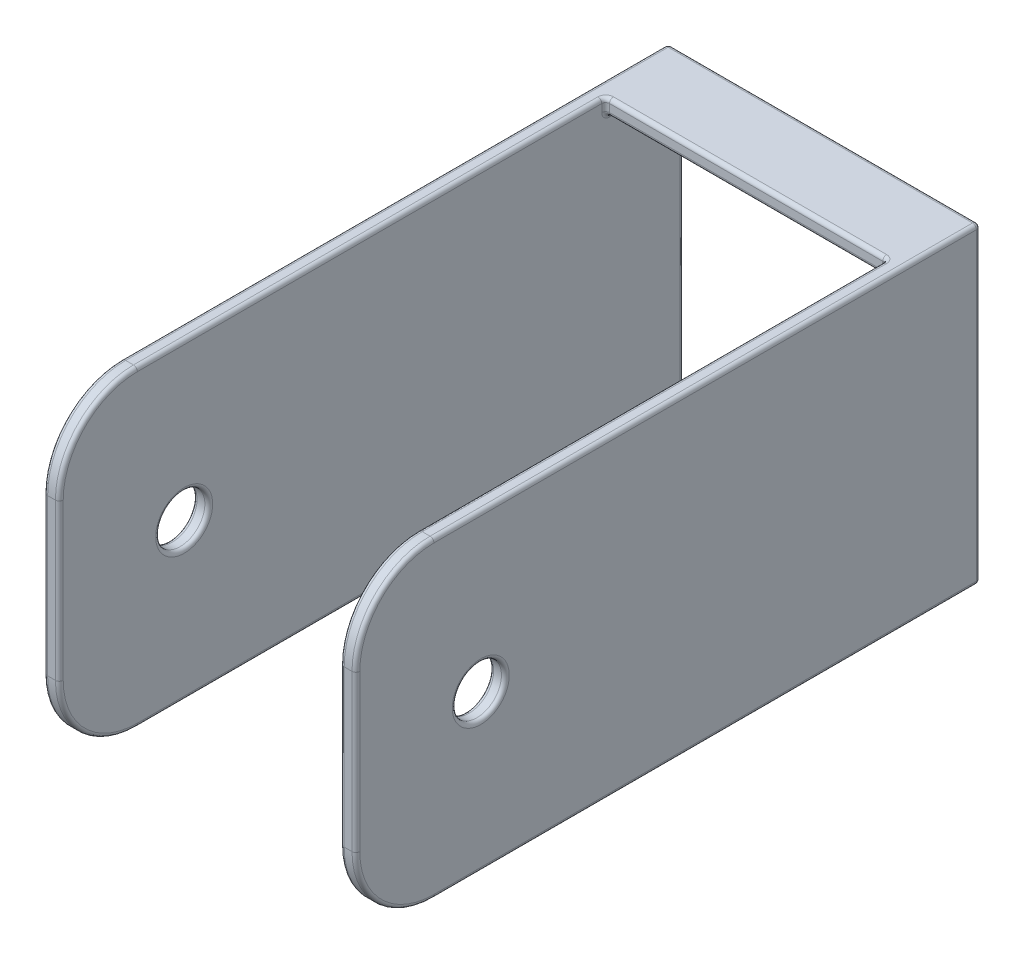
SolidWorks part; units mm, degrees
material "6061 Legierung"
ref_plane "Ebene vorne" through (0, 0, 0) normal (0, 0, 1) x (1, 0, 0)
ref_plane "Ebene oben" through (0, 0, 0) normal (0, 1, 0) x (1, 0, 0)
ref_plane "Ebene rechts" through (0, 0, 0) normal (1, 0, 0) x (0, 0, -1)
sketch "Skizze1" plane through (0, 0, 0) normal (0, 0, 1) x (1, 0, 0)
  line L1 (-20, -20) -> (20, -20)
  line L2 (-20, -20) -> (-20, 20)
  line L3 (-20, 20) -> (20, 20)
  line L4 (20, -20) -> (20, 20)
  line L5 (-20, -20) -> (20, 20) construction
  line L6 (-20, 20) -> (20, -20) construction
  line L7 (-18, -18) -> (18, -18)
  line L8 (-18, -18) -> (-18, 18)
  line L9 (-18, 18) -> (18, 18)
  line L10 (18, -18) -> (18, 18)
  line L11 (-18, -18) -> (18, 18) construction
  line L12 (-18, 18) -> (18, -18) construction
  point P0 (0, 0)
  point P6 (0, 0)
  dimension "D1" = 40
  dimension "D2" = 40
  dimension "D3" = 2
  dimension "D4" = 2
extrude "Aufsatz-Linear austragen1" add sketch "Skizze1" along normal blind 80
sketch "Skizze2" plane through (0, 20, 0) normal (0, 1, 0) x (1, 0, 0)
  line L0 (20, -80) -> (20, 0) construction
  line L1 (-18, -80) -> (18, -80)
  line L2 (-18, -80) -> (-18, -10)
  line L3 (-18, -10) -> (18, -10)
  line L4 (18, -80) -> (18, -10)
  line L5 (20, 0) -> (-20, 0) construction
  dimension "D1" = 2
  dimension "D2" = 10
extrude "Schnitt-Linear austragen1" cut sketch "Skizze2" against normal through all
sketch "Skizze3" plane through (20, 0, 0) normal (1, 0, 0) x (0, 0, -1)
  line L0 (-80, -20) -> (-80, 20) construction
  circle A0 centre (-64, 0) radius 3.15
  dimension "D1" = 6.3
  dimension "D2" = 16
extrude "Schnitt-Linear austragen2" cut sketch "Skizze3" against normal through all
fillet "Verrundung1" radius 10 4 edges at (-19, -20, 80) (19, -20, 80) (19, 20, 80) (-19, 20, 80)
fillet "Verrundung2" radius 0.5 44 edges at (0, -18, 0) (0, -18, 10) (0, 18, 0) (0, 18, 10) (-18, 17.0711, 77.0711) (-18, 19, 10) (-18, 18, 5) (-18, 0, 0) (-18, -18, 5) (-18, -19, 10) (-18, -17.0711, 77.0711) (-18, 0, 80) (-18, 0, 60.85) (18, -19, 10) (18, -18, 5) (18, 0, 0) (18, 18, 5) (18, 19, 10) (18, 17.0711, 77.0711) (18, 0, 80) (18, -17.0711, 77.0711) (18, 0, 67.15) (0, -20, 10) (18, -20, 40) (0, -20, 0) (-18, -20, 40) (0, 20, 10) (-18, 20, 40) (0, 20, 0) (18, 20, 40) (-20, 0, 0) (-20, 20, 35) (-20, 17.0711, 77.0711) (-20, 0, 80) (-20, -17.0711, 77.0711) (-20, -20, 35) (-20, 0, 60.85) (20, 17.0711, 77.0711) (20, 20, 35) (20, 0, 0) (20, -20, 35) (20, -17.0711, 77.0711) (20, 0, 80) (20, 0, 60.85)
